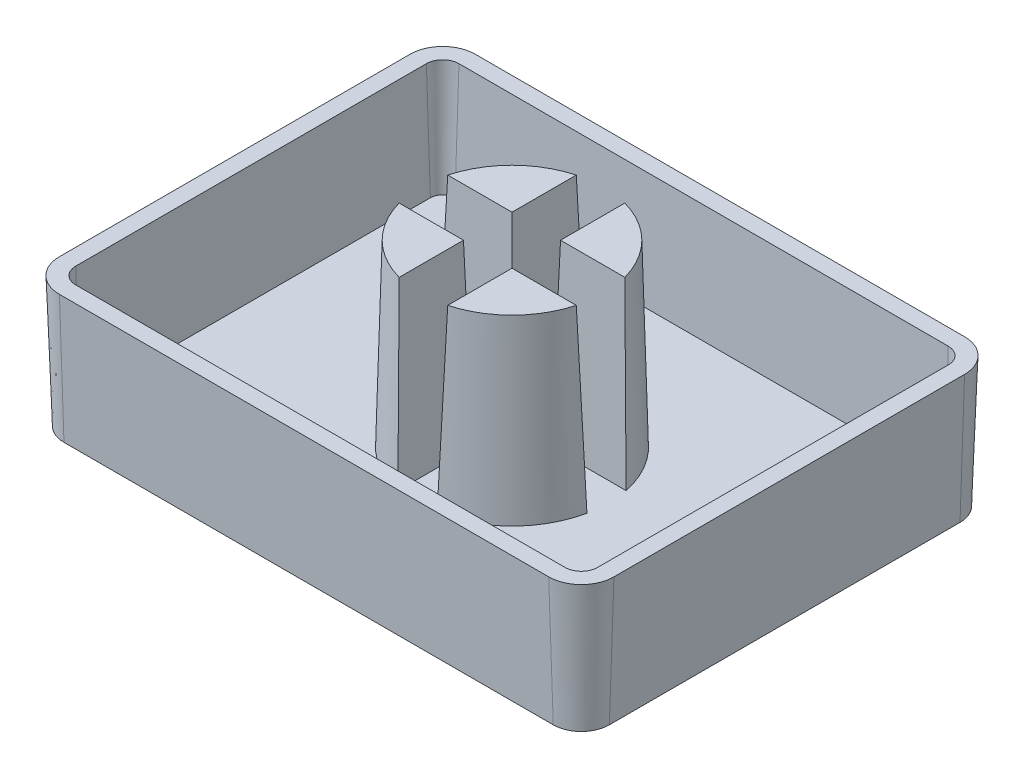
SolidWorks part; units mm, degrees
ref_plane "Front Plane" through (0, 0, 0) normal (0, 0, 1) x (1, 0, 0)
ref_plane "Top Plane" through (0, 0, 0) normal (0, 1, 0) x (1, 0, 0)
ref_plane "Right Plane" through (0, 0, 0) normal (1, 0, 0) x (0, 0, -1)
sketch "Sketch1" plane through (0, 0, 0) normal (0, 1, 0) x (1, 0, 0)
  line L1 (-7.5, -6.375) -> (7.5, -6.375)
  line L2 (-8.5, -5.375) -> (-8.5, 5.375)
  line L3 (-7.5, 6.375) -> (7.5, 6.375)
  line L4 (8.5, -5.375) -> (8.5, 5.375)
  line L5 (-8.5, -6.375) -> (8.5, 6.375) construction
  line L6 (-8.5, 6.375) -> (8.5, -6.375) construction
  arc A0 (-8.5, 5.375) -> (-7.5, 6.375) centre (-7.5, 5.375) cw
  arc A1 (8.5, 5.375) -> (7.5, 6.375) centre (7.5, 5.375) ccw
  arc A2 (8.5, -5.375) -> (7.5, -6.375) centre (7.5, -5.375) cw
  arc A3 (-7.5, -6.375) -> (-8.5, -5.375) centre (-7.5, -5.375) cw
  point P0 (0, 0)
  dimension "D3" = 1
  dimension "D1" = 17
  dimension "D2" = 12.75
extrude "Boss-Extrude1" add sketch "Sketch1" against normal blind 4 draft 2
shell "Shell1" thickness 0.5
sketch "Sketch3" plane through (0, -3.5, 0) normal (0, 1, 0) x (1, 0, 0)
  line L0 (-0.6, 2.8977) -> (-0.6, 0.6)
  line L1 (-2.8977, 0.6) -> (-0.6, 0.6)
  line L2 (0, -2.2) -> (0, 2.2) construction
  line L3 (-2.2, 0) -> (2.2, 0) construction
  line L4 (0.6, 2.8977) -> (0.6, 0.6)
  line L5 (-2.8977, -0.6) -> (-0.6, -0.6)
  line L6 (-0.6, -0.6) -> (-0.6, -2.8977)
  line L7 (0.6, -0.6) -> (0.6, -2.8977)
  line L8 (0.6, -0.6) -> (2.8977, -0.6)
  line L9 (0.6, 0.6) -> (2.8977, 0.6)
  arc A0 (-2.8977, -0.6) -> (-0.6, -2.8977) centre (0, 0) ccw
  arc A1 (2.8977, 0.6) -> (0.6, 2.8977) centre (0, 0) ccw
  arc A2 (0.6, -2.8977) -> (2.8977, -0.6) centre (0, 0) ccw
  arc A3 (-0.6, 2.8977) -> (-2.8977, 0.6) centre (0, 0) ccw
  dimension "D1" = 0.6
  dimension "D2" = 0.6
extrude "Boss-Extrude2" add sketch "Sketch3" along normal blind 5.5 draft 1.5
